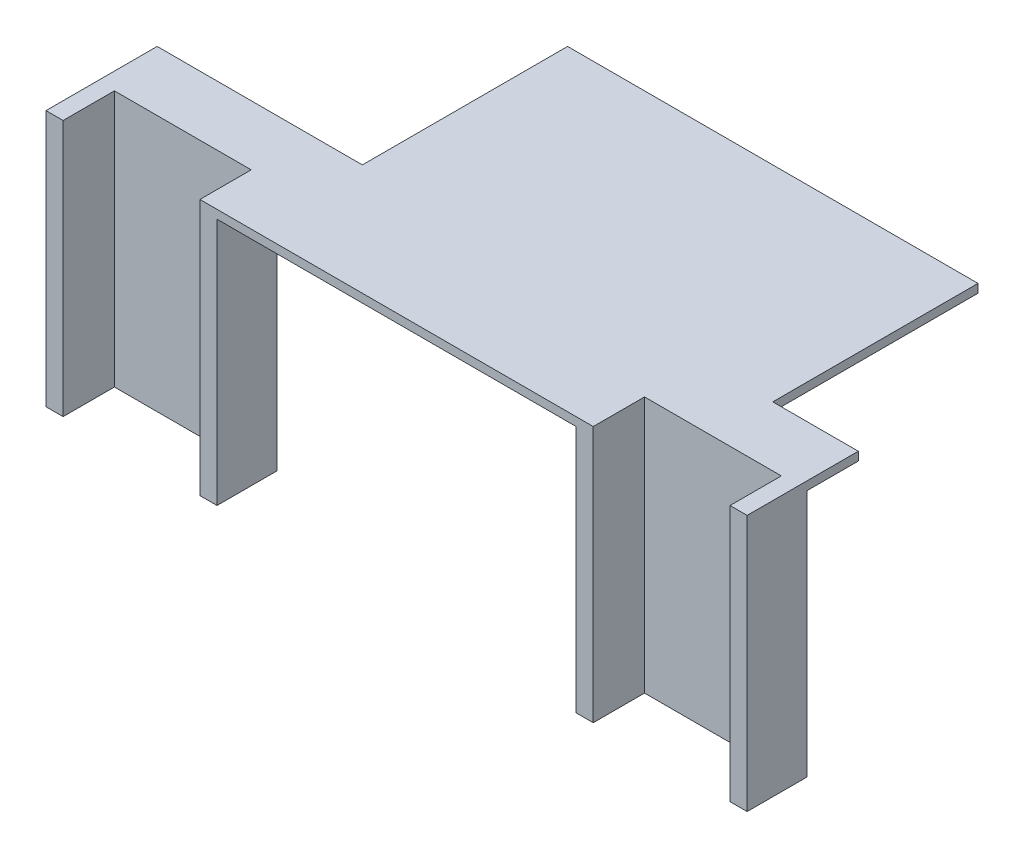
SolidWorks part; units mm, degrees
material "6063-O"
ref_plane "Front" through (0, 0, 0) normal (0, 0, 1) x (1, 0, 0)
ref_plane "Top" through (0, 0, 0) normal (0, 1, 0) x (1, 0, 0)
ref_plane "Right" through (0, 0, 0) normal (1, 0, 0) x (0, 0, -1)
sketch "Sketch1" plane through (0, 0, 0) normal (0, 0, 1) x (1, 0, 0)
  line L1 (0, 0) -> (410, 0)
  line L2 (0, 0) -> (0, 150)
  line L3 (0, 150) -> (410, 150)
  line L4 (410, 0) -> (410, 150)
  dimension "D1" = 150
  dimension "D2" = 410
extrude "Boss-Extrude1" add sketch "Sketch1" along normal blind 35
sketch "Sketch2" plane through (0, 0, 0) normal (0, 0, -1) x (-1, 0, 0)
  line L0 (0, 150) -> (0, 0) construction
  line L1 (-410, 150) -> (0, 150)
  line L2 (-410, 150) -> (-410, 145)
  line L3 (-410, 145) -> (0, 145)
  line L4 (0, 150) -> (0, 145)
  dimension "D1" = 5
extrude "Boss-Extrude2" add sketch "Sketch2" along normal blind 150
sketch "Sketch3" plane through (0, 0, 35) normal (0, 0, 1) x (1, 0, 0)
  line L0 (0, 0) -> (410, 0) construction
  line L1 (10, 0) -> (90, 0)
  line L2 (10, 0) -> (10, 150)
  line L3 (10, 150) -> (90, 150)
  line L4 (90, 0) -> (90, 150)
  line L5 (410, 150) -> (0, 150) construction
  line L6 (0, 150) -> (0, 0) construction
  line L7 (400, 0) -> (320, 0)
  line L8 (400, 0) -> (400, 150)
  line L9 (400, 150) -> (320, 150)
  line L10 (320, 0) -> (320, 150)
  line L11 (410, 0) -> (410, 150) construction
  dimension "D1" = 10
  dimension "D2" = 80
  dimension "D3" = 10
  dimension "D4" = 80
extrude "Cut-Extrude1" cut sketch "Sketch3" against normal blind 30
sketch "Sketch4" plane through (0, 0, 35) normal (0, 0, 1) x (1, 0, 0)
  line L0 (90, 0) -> (90, 150) construction
  line L1 (100, 145) -> (310, 145)
  line L2 (100, 145) -> (100, 0)
  line L3 (100, 0) -> (310, 0)
  line L4 (310, 145) -> (310, 0)
  line L5 (90, 0) -> (320, 0) construction
  line L6 (320, 150) -> (90, 150) construction
  line L7 (320, 150) -> (320, 0) construction
  dimension "D1" = 10
  dimension "D2" = 0
  dimension "D3" = 5
  dimension "D4" = 10
extrude "Cut-Extrude2" cut sketch "Sketch4" against normal blind 35
sketch "Sketch5" plane through (0, 150, 0) normal (0, 1, 0) x (1, 0, 0)
  line L1 (0, 150) -> (120, 150)
  line L2 (0, 150) -> (0, 30)
  line L3 (0, 30) -> (120, 30)
  line L4 (120, 150) -> (120, 30)
  dimension "D1" = 120
  dimension "D2" = 120
extrude "Cut-Extrude3" cut sketch "Sketch5" against normal blind 10
sketch "Sketch6" plane through (0, 150, 0) normal (0, 1, 0) x (1, 0, 0)
  line L1 (410, 150) -> (360, 150)
  line L2 (410, 150) -> (410, 30)
  line L3 (410, 30) -> (360, 30)
  line L4 (360, 150) -> (360, 30)
  dimension "D1" = 50
  dimension "D2" = 120
extrude "Cut-Extrude4" cut sketch "Sketch6" against normal blind 10
